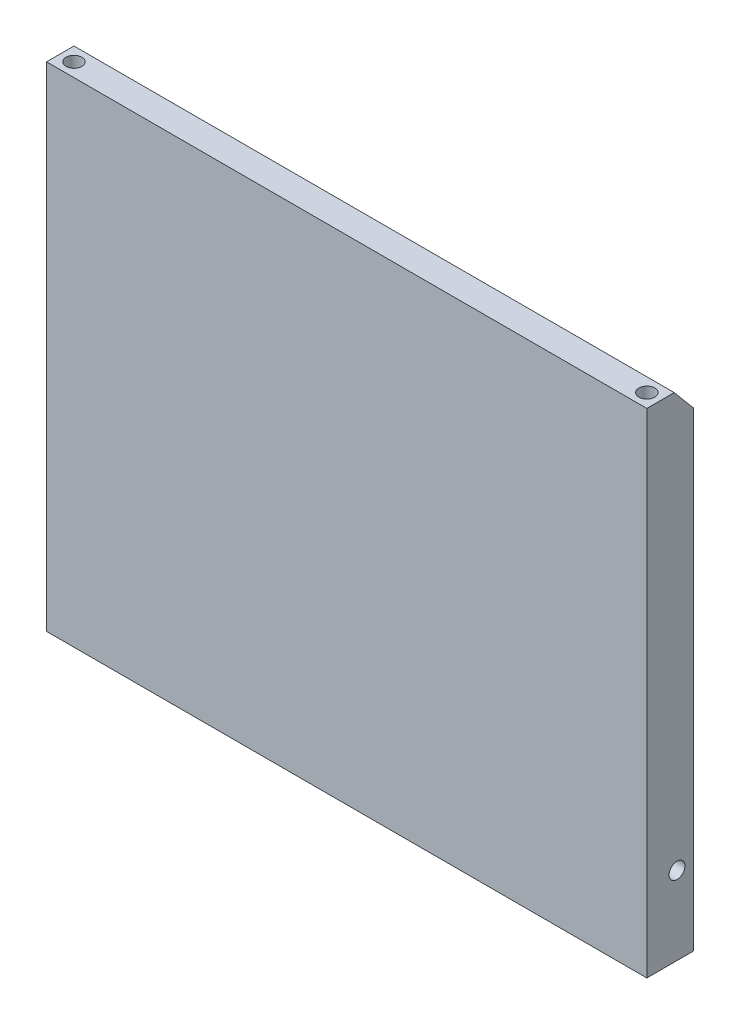
SolidWorks part; units mm, degrees
material "PLA"
ref_plane "Front Plane" through (0, 0, 0) normal (0, 0, 1) x (1, 0, 0)
ref_plane "Top Plane" through (0, 0, 0) normal (0, 1, 0) x (1, 0, 0)
ref_plane "Right Plane" through (0, 0, 0) normal (1, 0, 0) x (0, 0, -1)
sketch "Sketch1" plane through (0, 0, 0) normal (0, 0, 1) x (1, 0, 0)
  line L1 (-5.3066, -80.8019) -> (104.2134, -80.8019)
  line L2 (-5.3066, -80.8019) -> (-5.3066, 9.1981)
  line L3 (-5.3066, 9.1981) -> (104.2134, 9.1981)
  line L4 (104.2134, -80.8019) -> (104.2134, 9.1981)
  dimension "D1" = 109.52
  dimension "D2" = 90
extrude "Boss-Extrude1" add sketch "Sketch1" along normal blind 5
sketch "Sketch2" plane through (0, 9.1981, 0) normal (0, 1, 0) x (1, 0, 0)
  line L0 (-5.3066, -5) -> (-5.3066, 0) construction
  line L1 (104.2134, -5) -> (104.2134, 0) construction
  circle A0 centre (-2.8066, -2.5) radius 1.45
  circle A1 centre (101.7134, -2.5) radius 1.45
  point P7 (-5.3066, -2.5)
  dimension "D2" = 2.9
  dimension "D4" = 2.9
  dimension "D1" = 2.5
  dimension "D3" = 2.5
extrude "Cut-Extrude1" cut sketch "Sketch2" against normal blind 7 contours A1 | A0
sketch "Sketch4" plane through (0, 0, 0) normal (0, 0, -1) x (-1, 0, 0)
  line L4 (-104.2134, 9.1981) -> (-104.2134, -80.8019)
  line L5 (-104.2134, -80.8019) -> (5.3066, -80.8019)
  line L6 (5.3066, -80.8019) -> (5.3066, 9.1981)
  line L7 (5.3066, 9.1981) -> (-104.2134, 9.1981)
  line L8 (-104.2134, 9.1981) -> (-104.2134, -80.8019)
  line L9 (-104.2134, -80.8019) -> (5.3066, -80.8019)
  line L10 (5.3066, -80.8019) -> (5.3066, 9.1981)
  line L11 (5.3066, 9.1981) -> (-104.2134, 9.1981)
  dimension "D1" = 0
extrude "Boss-Extrude2" add sketch "Sketch4" along normal blind 3.5
sketch "Sketch5" plane through (0, 0, -3.5) normal (0, 0, -1) x (-1, 0, 0)
  line L0 (-49.4534, 9.1981) -> (-49.4534, -80.8019) construction
  line L1 (-99.5534, 3.7981) -> (0.6466, 3.7981)
  line L2 (-99.5534, 3.7981) -> (-99.5534, -75.4019)
  line L3 (-99.5534, -75.4019) -> (0.6466, -75.4019)
  line L4 (0.6466, 3.7981) -> (0.6466, -75.4019)
  line L5 (5.3066, 9.1981) -> (-104.2134, 9.1981) construction
  line L6 (-104.2134, -80.8019) -> (5.3066, -80.8019) construction
  point P10 (-49.4534, 3.7981)
  point P11 (-99.5534, -35.8019)
  point P12 (-49.4534, -35.8019)
  dimension "D1" = 100.2
  dimension "D2" = 79.2
chamfer "Chamfer1" distance 3.5 angle 50 1 edges at (49.4534, 9.1981, -3.5)
ref_plane "Plane1" through (49.4534, 0, 0) normal (-1, 0, 0) x (0, 0, 1)
extrude "Cut-Extrude3" cut sketch "Sketch5" against normal blind 6.5
sketch "Sketch8" plane through (104.2134, 0, 0) normal (1, 0, 0) x (0, 0, -1)
  line L2 (0.5, -68.0019) -> (0.5, -65.1019) construction
  circle A2 centre (0.5, -66.5519) radius 1.45
extrude "Cut-Extrude5" cut sketch "Sketch8" against normal blind 3
mirror "Mirror2" about plane through (49.4534, 0, 0) normal (-1, 0, 0) of "Cut-Extrude5"
